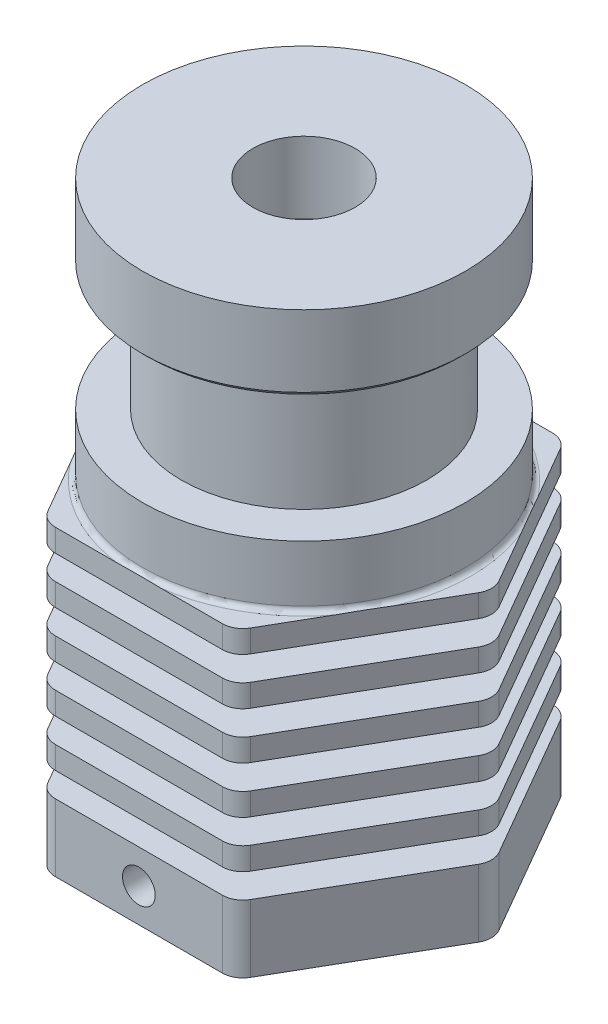
SolidWorks part; units mm, degrees
material "7075-T6, Plate (SS)"
ref_plane "Front" through (0, 0, 0) normal (0, 0, 1) x (1, 0, 0)
ref_plane "Top" through (0, 0, 0) normal (0, 1, 0) x (1, 0, 0)
ref_plane "Right" through (0, 0, 0) normal (1, 0, 0) x (0, 0, -1)
sketch "Sketch1" plane through (0, 0, 0) normal (1, 0, 0) x (0, 0, -1)
  line L0 (0, 57.6214) -> (0, 0) construction
  line L1 (0, 0) -> (20, 0) construction
  line L2 (3, 0) -> (3, 3)
  line L3 (3, 3) -> (1.55, 3)
  line L4 (1.55, 3) -> (1.55, 24.1)
  line L5 (1.55, 24.1) -> (2.5, 24.1)
  line L6 (2.5, 24.1) -> (2.5, 28.6)
  line L7 (2.5, 28.6) -> (7.9, 28.6)
  line L8 (7.9, 28.6) -> (7.9, 23.85)
  line L9 (7.9, 23.85) -> (6, 23.85)
  line L10 (6, 23.85) -> (6, 19.3)
  line L11 (6, 19.3) -> (7.9, 19.3)
  line L12 (7.9, 19.3) -> (7.9, 14.8)
  line L13 (7.9, 14.8) -> (10, 14.8)
  line L14 (10, 14.8) -> (10, 13.7)
  line L15 (10, 13.7) -> (4.825, 13.7)
  line L16 (4.825, 13.7) -> (4.825, 12.5)
  line L17 (4.825, 12.5) -> (10, 12.5)
  line L18 (10, 12.5) -> (10, 11.4)
  line L19 (10, 11.4) -> (4.825, 11.4)
  line L20 (4.825, 11.4) -> (4.825, 10.2)
  line L21 (4.825, 10.2) -> (10, 10.2)
  line L22 (10, 10.2) -> (10, 9.1)
  line L23 (10, 9.1) -> (4.825, 9.1)
  line L24 (4.825, 9.1) -> (4.825, 7.9)
  line L25 (4.825, 7.9) -> (10, 7.9)
  line L26 (10, 7.9) -> (10, 6.8)
  line L27 (10, 6.8) -> (4.825, 6.8)
  line L28 (4.825, 6.8) -> (4.825, 5.6)
  line L29 (4.825, 5.6) -> (10, 5.6)
  line L30 (10, 5.6) -> (10, 4.5)
  line L31 (10, 4.5) -> (4.825, 4.5)
  line L32 (4.825, 4.5) -> (4.825, 3.3)
  line L33 (4.825, 3.3) -> (10, 3.3)
  line L34 (10, 3.3) -> (10, 0)
  line L35 (10, 0) -> (3, 0)
  dimension "D1" = 1.1
  dimension "D2" = 1.2
  dimension "D3" = 3
  dimension "D4" = 6
  dimension "D5" = 20
  dimension "D6" = 3.1
  dimension "D7" = 5
  dimension "D8" = 3.3
  dimension "D9" = 9.65
  dimension "D10" = 15.8
  dimension "D11" = 4.5
  dimension "D12" = 4.75
  dimension "D13" = 12
  dimension "D14" = 4.5
  dimension "D15" = 28.6
revolve "Revolve1" add sketch "Sketch1" angle 360 about L0
cosmetic thread "Cosmetic Thread1" parameters "D2"=6
fillet "Fillet1" radius 0.25 1 edges at (0, 14.8, 7.9)
sketch "Sketch2" plane through (0, 28.6, 0) normal (0, 1, 0) x (1, 0, 0)
  line L1 (-4.0848, -8.075) -> (4.0848, -8.075)
  line L2 (4.9508, -7.575) -> (9.0355, -0.5)
  line L3 (9.0355, 0.5) -> (4.9508, 7.575)
  line L4 (4.0848, 8.075) -> (-4.0848, 8.075)
  line L5 (-4.9508, 7.575) -> (-9.0355, 0.5)
  line L6 (-9.0355, -0.5) -> (-4.9508, -7.575)
  circle A0 centre (0, 0) radius 8.075 construction
  arc A1 (-9.0355, 0.5) -> (-9.0355, -0.5) centre (-8.1695, 0) ccw
  arc A2 (-4.0848, -8.075) -> (-4.9508, -7.575) centre (-4.0848, -7.075) cw
  arc A3 (4.0848, -8.075) -> (4.9508, -7.575) centre (4.0848, -7.075) ccw
  arc A4 (9.0355, -0.5) -> (9.0355, 0.5) centre (8.1695, 0) ccw
  arc A5 (4.9508, 7.575) -> (4.0848, 8.075) centre (4.0848, 7.075) ccw
  arc A6 (-4.0848, 8.075) -> (-4.9508, 7.575) centre (-4.0848, 7.075) ccw
  dimension "D2" = 1
  dimension "D1" = 16.15
extrude "Cut-Extrude1" cut sketch "Sketch2" against normal through all flip side to cut
sketch "Sketch3" plane through (0, 0, 8.075) normal (0, 0, 1) x (1, 0, 0)
  line L0 (0, 0) -> (0, 3.3) construction
  line L1 (4.0848, 3.3) -> (-4.0848, 3.3) construction
hole_wizard "M2 Tapped Hole1" positions "Sketch5" profile "Sketch4" tap size "M2" standard "ISO"
sketch "Sketch5" plane through (0, 0, 8.075) normal (0, 0, 1) x (1, 0, 0)
  line L0 (0, 0) -> (0, 3.3) construction
  point P0 (0, 1.65)
sketch "Sketch4" plane through (0, 1.65, 8.075) normal (1, 0, 0) x (0, -1, 0)
  line L0 (0, 0) -> (0, 5.075)
  line L1 (0, 5.075) -> (0.8, 5.075)
  line L2 (0.8, 5.075) -> (0.8, 0)
  line L5 (0.8, 0) -> (0, 0)
  line L11 (0, -6.35) -> (0, 107.95) construction
  dimension "Thru Tap Drill Dia." = 1.6
  dimension "Thru Tap Drill Depth" = 5.075
cosmetic thread "Hole Thread1" parameters "D2"=2
chamfer "Chamfer1" distance 0.25 angle 45 3 edges at (0, 28.6, 7.9) (0, 19.3, 7.9) (0, 23.85, 7.9)
chamfer "Chamfer2" distance 0.5 angle 45 1 edges at (0, 28.6, 2.5)
sketch "Sketch6" plane through (0, 28.6, 0) normal (0, 1, 0) x (1, 0, 0)
  circle A0 centre (0, 0) radius 7.9 construction
  circle A1 centre (0, 0) radius 7.9
extrude "Cut-Extrude2" cut sketch "Sketch6" against normal blind 1
sketch "Sketch7" plane through (0, 0, 0) normal (1, 0, 0) x (0, 0, -1)
  line L0 (0, 0) -> (0, 21.8723) construction
  line L1 (6, 19.3) -> (6, 23.85) construction
  line L2 (6, 19.3) -> (10, 19.3)
  line L3 (6, 19.3) -> (6, 17.8)
  line L4 (6, 17.8) -> (10, 17.8)
  line L5 (10, 19.3) -> (10, 17.8)
  line L6 (7.65, 19.3) -> (-7.65, 19.3) construction
  dimension "D1" = 1.5
  dimension "D2" = 20
revolve "Cut-Revolve1" cut sketch "Sketch7" angle 360 about L0
sketch "Sketch8" plane through (0, 0, 0) normal (0, -1, 0) x (1, 0, 0)
  line L0 (-8.7436, -2.729) -> (-14.5, 33.075)
  line L1 (8.65, -3.3114) -> (14.5, 33.075)
  line L2 (-9.1823, 0) -> (9.1823, 0) construction
  line L3 (-14.5, 33.075) -> (14.5, 33.075) construction
  line L4 (-4.0848, 8.075) -> (4.0848, 8.075) construction
  line L5 (0, 0) -> (0, 33.075) construction
  arc A0 (9.0355, -0.5) -> (9.0355, 0.5) centre (8.1695, 0) ccw construction
  arc A1 (-9.0355, 0.5) -> (-9.0355, -0.5) centre (-8.1695, 0) ccw construction
  dimension "D1" = 25
  dimension "D2" = 29
sketch "Sketch9" plane through (0, 0, 0) normal (1, 0, 0) x (0, 0, -1)
  line L0 (-8.075, 14.8115) -> (-30.4217, 14.8115) construction
  line L1 (-20.5456, 14.9439) -> (-20.075, 14.0615)
  line L2 (-20.075, 14.0615) -> (-16.2678, 14.0615)
  line L3 (-23.577, 13.0761) -> (-11.0457, 13.8115) construction
  line L4 (-8.075, 14.8115) -> (-8.075, 13.8115) construction
  line L5 (-11.075, 14.8115) -> (-23.6356, 14.0744) construction
  line L6 (-26.2493, 14.3836) -> (-35.3368, 17.1364) construction
  line L7 (-35.0701, 16.0107) -> (-26.5393, 13.4266) construction
  line L8 (-35.3368, 17.1364) -> (-35.0701, 16.0107) construction
  line L9 (-35.0701, 16.0107) -> (-28.3846, -12.2081) construction
  line L10 (-8.075, 1.1982) -> (-8.075, 0) construction
  line L11 (0, 0) -> (-33.075, 0) construction
  line L12 (-8.075, 0) -> (-28.1391, -13.2443) construction
  line L13 (-8.075, 1.1982) -> (-28.3846, -12.2081) construction
  line L14 (-8.075, 13.8115) -> (-11.0457, 13.8115) construction
  line L15 (-8.075, 13.8115) -> (-8.075, 1.1982) construction
  line L16 (-8.075, 7.5049) -> (-31.7273, 1.9013) construction
  line L17 (-28.3846, -12.2081) -> (-28.1391, -13.2443) construction
  line L18 (-44.916, 14.1919) -> (-35.1853, 16.4973) construction
  line L19 (-38, -15) -> (-44.916, 14.1919) construction
  line L20 (-31.7273, 1.9013) -> (-41.458, -0.404) construction
  line L21 (-38, -15) -> (-28.2694, -12.6947) construction
  line L22 (0, 0) -> (0, -15) construction
  line L23 (0, -15) -> (-38, -15) construction
  line L24 (-44.916, 14.1919) -> (-44.916, -12.9102) construction
  circle A0 centre (-24.075, 21.5615) radius 7.5
  arc A1 (-14.8984, 28.5753) -> (-14.6328, 14.9097) centre (-24.075, 21.5615) cw
  arc A2 (-16.2678, 14.0615) -> (-14.6328, 14.9097) centre (-16.2678, 16.0615) ccw
  arc A4 (-26.5393, 13.4266) -> (-23.577, 13.0761) centre (-24.075, 21.5615) ccw construction
  dimension "D1" = 15
  dimension "D4" = 11.55
  dimension "D5" = 2
  dimension "D2" = 16
  dimension "D3" = 6.75
  dimension "D6" = 1
  dimension "D7" = 3
  dimension "D8" = 1
  dimension "D9" = 1
  dimension "D10" = 1
  dimension "D11" = 29
  dimension "D12" = 10
  dimension "D13" = 30
  dimension "D14" = 15
  dimension "D15" = 38
  dimension "D16" = 13.328
ref_plane "Plane1" through (0, 1.9013, 31.7273) normal (0, -0.2305, 0.9731) x (1, 0, 0)
